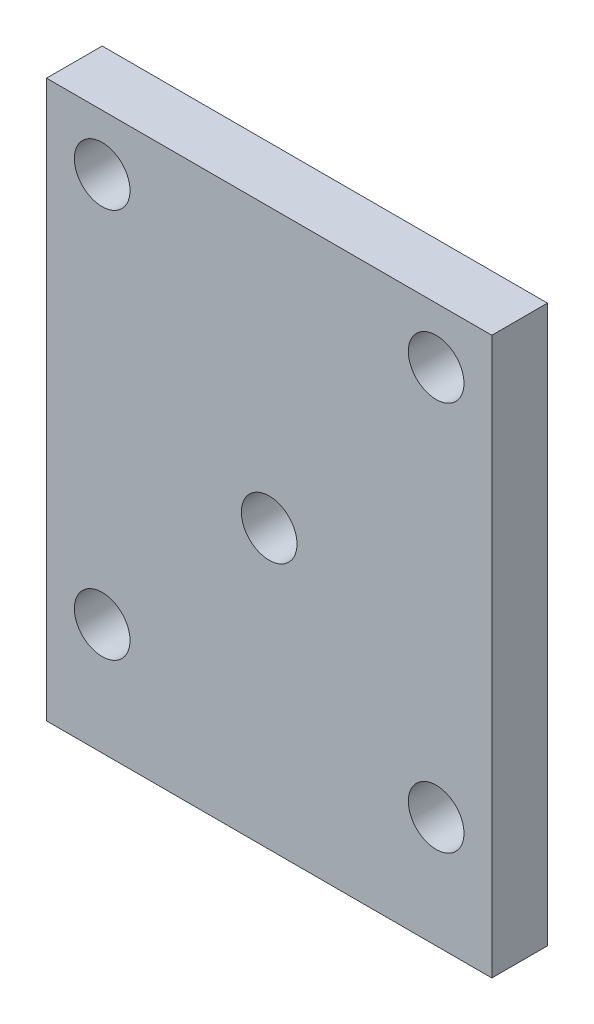
SolidWorks part; units mm, degrees
material "6061 Alloy"
ref_plane "Front" through (0, 0, 0) normal (0, 0, 1) x (1, 0, 0)
ref_plane "Top" through (0, 0, 0) normal (0, 1, 0) x (1, 0, 0)
ref_plane "Right" through (0, 0, 0) normal (1, 0, 0) x (0, 0, -1)
sketch "Sketch1" plane through (0, 0, 0) normal (0, 0, 1) x (1, 0, 0)
  line L1 (0, 0) -> (101.6, 0)
  line L2 (0, 0) -> (0, 127)
  line L3 (0, 127) -> (101.6, 127)
  line L4 (101.6, 0) -> (101.6, 127)
  dimension "D1" = 101.6
  dimension "D2" = 127
extrude "Boss-Extrude1" add sketch "Sketch1" along normal blind 19.05
sketch "Sketch2" plane through (0, 0, 0) normal (0, 0, -1) x (-1, 0, 0)
  line L0 (0, 0) -> (-101.6, 0) construction
  line L1 (-101.6, 127) -> (-76.2, 127)
  line L2 (-101.6, 127) -> (-101.6, 0)
  line L3 (-101.6, 0) -> (-76.2, 0)
  line L4 (-76.2, 127) -> (-76.2, 0)
  line L5 (-50.8, 105.5447) -> (-50.8, -5.5939) construction
  line L6 (-25.4, 127) -> (-25.4, 0)
  line L7 (0, 0) -> (-25.4, 0)
  line L8 (0, 127) -> (0, 0)
  line L9 (0, 127) -> (-25.4, 127)
  dimension "D1" = 25.4
  dimension "D2" = 50.8
extrude "Cut-Extrude1" cut sketch "Sketch2" against normal blind 6.35
sketch "Sketch4" plane through (0, 0, 19.05) normal (0, 0, 1) x (1, 0, 0)
  line L0 (0, 127) -> (0, 0) construction
  line L2 (50.8, 105.5447) -> (50.8, -4.7693) construction
  line L3 (0, 0) -> (101.6, 0) construction
  circle A0 centre (12.7, 114.3) radius 6.35
  circle A1 centre (12.7, 25.4) radius 6.35
  circle A2 centre (88.9, 25.4) radius 6.35
  circle A3 centre (88.9, 114.3) radius 6.35
  dimension "D1" = 12.7
  dimension "D2" = 12.7
  dimension "D3" = 12.7
  dimension "D4" = 25.4
  dimension "D6" = 88.9
extrude "Cut-Extrude2" cut sketch "Sketch4" against normal up to next
sketch "Sketch9" plane through (0, 0, 0) normal (0, 0, -1) x (-1, 0, 0)
  line L0 (-25.4, 127) -> (-25.4, 0) construction
  line L1 (-76.2, 0) -> (-25.4, 0)
  line L2 (-76.2, 0) -> (-76.2, 50.8)
  line L3 (-76.2, 50.8) -> (-25.4, 50.8)
  line L4 (-25.4, 0) -> (-25.4, 50.8)
  line L5 (-25.4, 127) -> (-25.4, 0) construction
  line L6 (-76.2, 127) -> (-25.4, 127)
  line L7 (-76.2, 127) -> (-76.2, 76.2)
  line L8 (-76.2, 76.2) -> (-25.4, 76.2)
  line L9 (-25.4, 127) -> (-25.4, 76.2)
  dimension "D1" = 50.8
  dimension "D2" = 50.8
extrude "Cut-Extrude7" cut sketch "Sketch9" along direction (0, 0, -1) on the side against the normal up to surface (6.35 mm away)
sketch "Sketch11" plane through (0, 0, 19.05) normal (0, 0, 1) x (1, 0, 0)
  line L0 (101.6, 0) -> (101.6, 127) construction
  line L1 (0, 0) -> (101.6, 0) construction
  circle A0 centre (50.8, 63.5) radius 6.35
  dimension "D1" = 12.7
  dimension "D2" = 50.8
  dimension "D3" = 63.5
extrude "Cut-Extrude8" cut sketch "Sketch11" against normal blind 9.525
